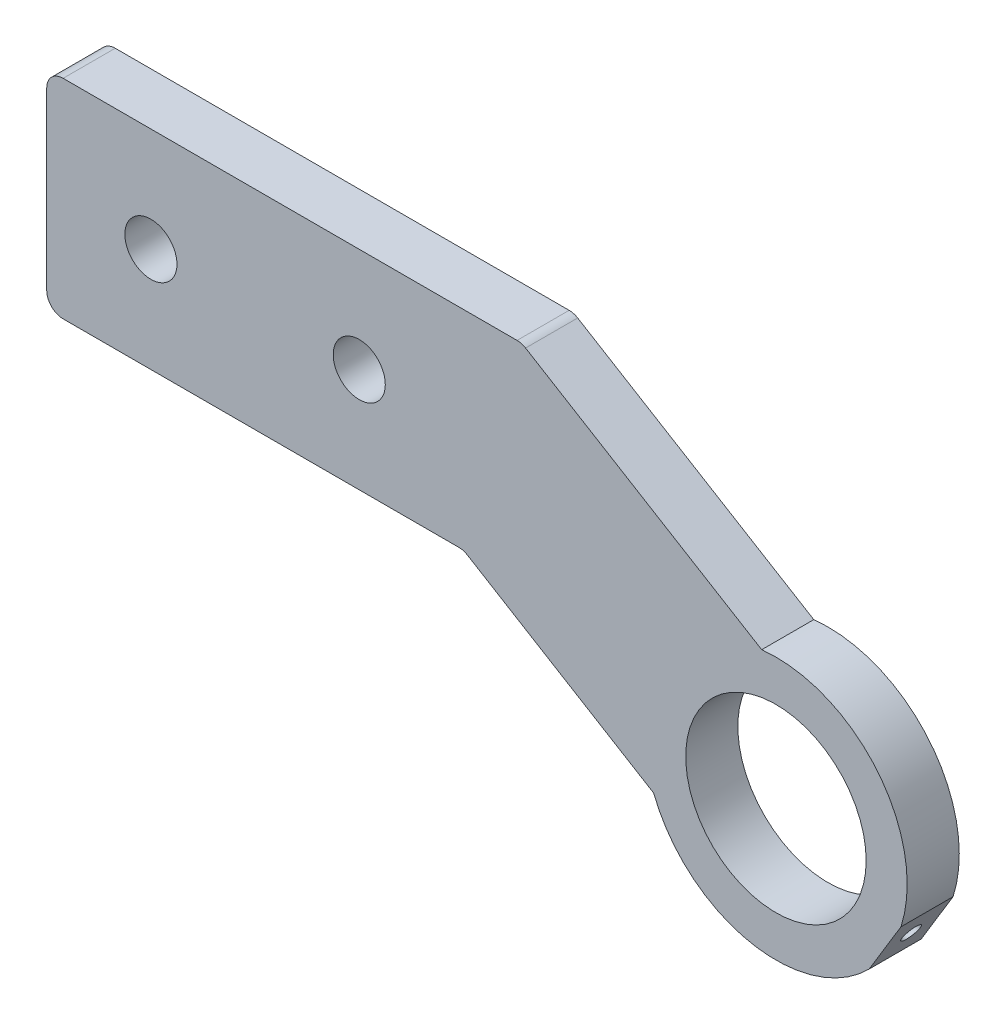
SolidWorks part; units mm, degrees
ref_plane "Front Plane" through (0, 0, 0) normal (0, 0, 1) x (1, 0, 0)
ref_plane "Top Plane" through (0, 0, 0) normal (0, 1, 0) x (1, 0, 0)
ref_plane "Right Plane" through (0, 0, 0) normal (1, 0, 0) x (0, 0, -1)
sketch "Sketch1" plane through (0, 0, 0) normal (0, 0, 1) x (1, 0, 0)
  line L0 (-25.4, 0) -> (-38.1, 0) construction
  line L2 (-38.1, -12.7) -> (-38.1, 12.7)
  line L5 (57.3848, -10.0904) -> (44.2152, -31.8096) construction
  line L6 (12.7, -12.7) -> (35.8936, -26.7637) construction
  line L19 (-25.4, 0) -> (0, 0) construction
  line L25 (19.7992, 12.7) -> (-38.1, 12.7)
  line L26 (12.7, -12.7) -> (-38.1, -12.7)
  line L27 (19.7992, 12.7) -> (49.0632, -5.0445)
  line L28 (50.8, -20.95) -> (85.0003, -41.6877) construction
  line L29 (66.0446, -25.8082) -> (62.1559, -32.2213)
  line L30 (12.7, -12.7) -> (35.8936, -26.7637)
  circle A0 centre (-25.4, 0) radius 3.175
  circle A12 centre (0, 0) radius 3.175
  circle A13 centre (50.8, -20.95) radius 11
  circle A14 centre (50.8, -20.95) radius 16 construction
  arc A15 (62.1559, -32.2213) -> (35.8936, -26.7637) centre (50.8, -20.95) cw
  arc A16 (49.0632, -5.0445) -> (66.0446, -25.8082) centre (50.8, -20.95) cw
  point P13 (64.1003, -29.0148)
  dimension "D4" = 6.35
  dimension "D7" = 5
  dimension "D8" = 25.4
  dimension "D10" = 7.5
  dimension "D5" = 50.8
  dimension "D6" = 20.95
  dimension "D9" = 22
  dimension "D2" = 50.8
  dimension "D3" = 12.7
  dimension "D12" = 25.4
  dimension "D13" = 25.4
extrude "Boss-Extrude1" add sketch "Sketch1" along normal blind 6.35
fillet "Fillet3" radius 2 4 edges at (-38.1, -12.7, 3.175) (-38.1, 12.7, 3.175) (19.7992, 12.7, 3.175) (12.7, -12.7, 3.175)
sketch "Sketch2" plane through (59.7319, -36.2191, 0) normal (0.8551, -0.5185, 0) x (0, 0, -1)
  line L0 (-6.35, 8.4252) -> (0, 8.4252) construction
  line L1 (-6.35, 4.6752) -> (-6.35, 12.1752) construction
  line L2 (0, 4.6752) -> (0, 12.1752) construction
  circle A0 centre (-3.175, 8.4252) radius 1.1303
  dimension "D1" = 2.2606
extrude "Cut-Extrude1" cut sketch "Sketch2" against normal up to next
